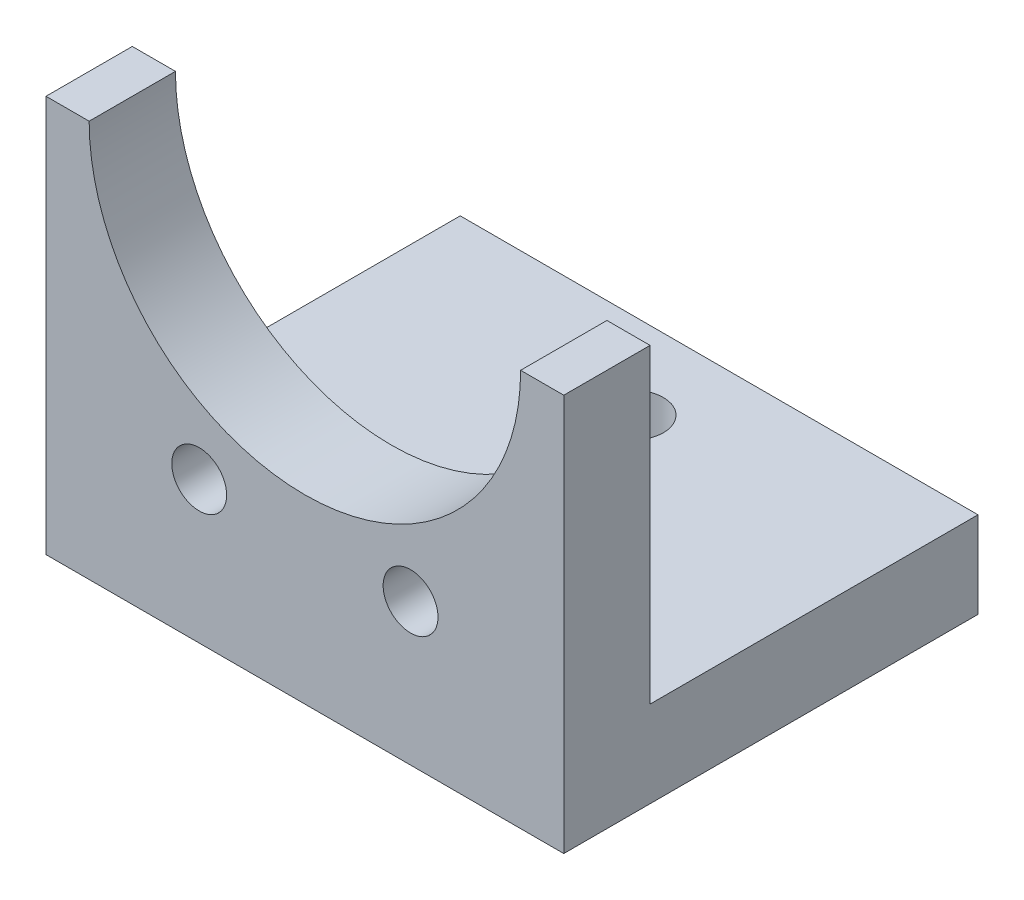
SolidWorks part; units mm, degrees
ref_plane "Front Plane" through (0, 0, 0) normal (0, 0, 1) x (1, 0, 0)
ref_plane "Top Plane" through (0, 0, 0) normal (0, 1, 0) x (1, 0, 0)
ref_plane "Right Plane" through (0, 0, 0) normal (1, 0, 0) x (0, 0, -1)
sketch "Sketch1" plane through (0, 0, 0) normal (0, 1, 0) x (1, 0, 0)
  line L1 (-19.05, 12.7) -> (19.05, 12.7)
  line L2 (-19.05, 12.7) -> (-19.05, -17.78)
  line L3 (-19.05, -17.78) -> (19.05, -17.78)
  line L4 (19.05, 12.7) -> (19.05, -17.78)
  dimension "D1" = 30.48
  dimension "D2" = 38.1
extrude "Extrude1" add sketch "Sketch1" along normal blind 6.35
ref_plane "Plane1" through (0, 6.35, 0) normal (0, 1, 0) x (-1, 0, 0)
sketch "Sketch2" plane through (0, 6.35, 0) normal (0, 1, 0) x (-1, 0, 0)
  line L0 (-19.05, 17.78) -> (-19.05, -12.7) construction
  line L1 (19.05, 17.78) -> (-19.05, 17.78)
  line L2 (19.05, 17.78) -> (19.05, 11.43)
  line L3 (19.05, 11.43) -> (-19.05, 11.43)
  line L4 (-19.05, 17.78) -> (-19.05, 11.43)
  dimension "D1" = 6.35
extrude "Extrude2" add sketch "Sketch2" along normal blind 22.86
sketch "Sketch3" plane through (0, 6.35, 0) normal (0, 1, 0) x (-1, 0, 0)
  point P0 (0, 6.35)
  point P1 (0, -6.35)
hole_wizard "#16 (0.177) Diameter Hole3" positions "3DSketch1" profile "Sketch4" hole size "#16" standard "Ansi Inch"
sketch3d "3DSketch1"
  point P0 (0, 6.35, 6.35)
  point P3 (0, 6.35, -6.35)
sketch "Sketch4" plane through (0, 6.35, 6.35) normal (1, 0, 0) x (0, 0, 1)
  line L0 (0, 0) -> (0, 59.7707)
  line L1 (0, 59.7707) -> (2.2479, 58.42)
  line L2 (2.2479, 58.42) -> (2.2479, 0)
  line L5 (2.2479, 0) -> (0, 0)
  line L10 (0, 59.7707) -> (-2.2479, 58.42) construction
  line L11 (0, -6.35) -> (0, 107.95) construction
  dimension "Hole Dia." = 4.4958
  dimension "Hole Depth" = 58.42
  dimension "Drill Angle" = 118
ref_plane "Plane2" through (0, 0, 17.78) normal (0, 0, 1) x (1, 0, 0)
sketch "Sketch6" plane through (0, 0, 17.78) normal (0, 0, 1) x (1, 0, 0)
  line L0 (-19.05, 29.21) -> (19.05, 29.21) construction
  circle A0 centre (0, 29.21) radius 15.875
  dimension "D1" = 31.75
extrude "Cut-Extrude2" cut sketch "Sketch6" against normal blind 25.4
sketch "Sketch7" plane through (0, 0, 17.78) normal (0, 0, 1) x (1, 0, 0)
  line L0 (0, 29.21) -> (0, 18.0686)
  line L1 (0, 29.21) -> (7.7761, 10.4368)
  point P0 (0, 29.21)
  point P1 (7.7761, 10.4368)
  dimension "D1" = 22.5
  dimension "D2" = 20.32
hole_wizard "#10-32 Tapped Hole1" positions "3DSketch2" profile "Sketch9" tap size "#10-32" standard "Ansi Inch" end condition through all
sketch3d "3DSketch2"
  point P0 (7.7761, 10.4368, 17.78)
sketch "Sketch9" plane through (7.7761, 10.4368, 17.78) normal (1, 0, 0) x (0, -1, 0)
  line L0 (0, 0) -> (0, 30.48)
  line L1 (0, 30.48) -> (2.0193, 30.48)
  line L2 (2.0193, 30.48) -> (2.0193, 0)
  line L5 (2.0193, 0) -> (0, 0)
  line L11 (0, -6.35) -> (0, 107.95) construction
  dimension "Thru Tap Drill Dia." = 4.0386
  dimension "Thru Tap Drill Depth" = 30.48
cosmetic thread "Hole Thread3" parameters "D2"=4.826
ref_axis "Axis1" through (0, 29.21, 35.2072) along (0, 0, -1)
pattern_circular "CirPattern1" count 2 over 45 about axis through (0, 29.21, 35.2072) along (0, 0, -1) of "#10-32 Tapped Hole1"
sketch "Sketch10" plane through (0, 6.35, 0) normal (0, 1, 0) x (-1, 0, 0)
  circle A0 centre (0, 6.35) radius 4.0894
  dimension "D1" = 8.1788
